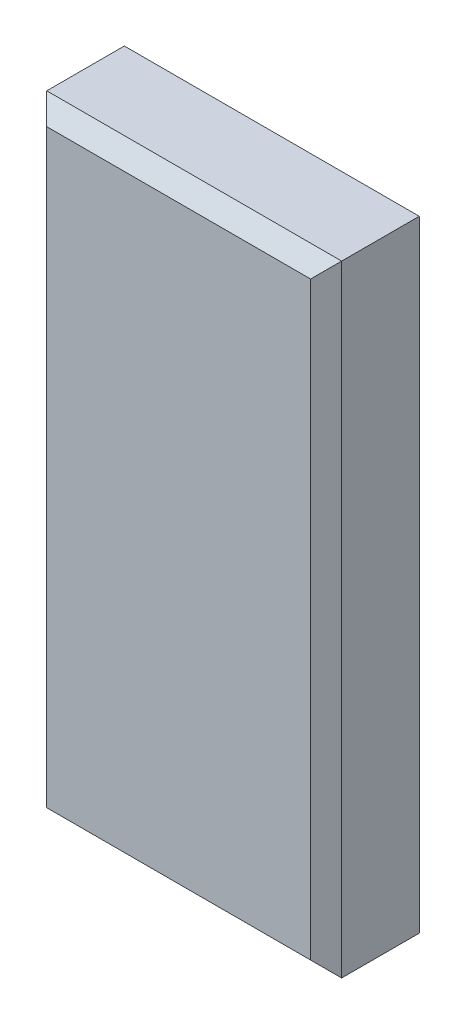
SolidWorks part; units mm, degrees
ref_plane "Front Plane" through (0, 0, 0) normal (0, 0, 1) x (1, 0, 0)
ref_plane "Top Plane" through (0, 0, 0) normal (0, 1, 0) x (1, 0, 0)
ref_plane "Right Plane" through (0, 0, 0) normal (1, 0, 0) x (0, 0, -1)
sketch "Sketch1" plane through (0, 0, 0) normal (0, 0, 1) x (1, 0, 0)
  line L1 (-9.5, 20) -> (9.5, 20)
  line L2 (-9.5, 20) -> (-9.5, -20)
  line L3 (-9.5, -20) -> (9.5, -20)
  line L4 (9.5, 20) -> (9.5, -20)
  line L5 (-9.5, 20) -> (9.5, -20) construction
  line L6 (-9.5, -20) -> (9.5, 20) construction
  point P0 (0, 0)
  dimension "D1" = 19
  dimension "D2" = 40
extrude "Boss-Extrude1" add sketch "Sketch1" along normal blind 7
chamfer "Chamfer1" distance 1 angle 45 8 edges at (0, 20, 0) (-9.5, 0, 0) (0, -20, 0) (9.5, 0, 0) (0, -20, 7) (-9.5, 0, 7) (0, 20, 7) (9.5, 0, 7)
